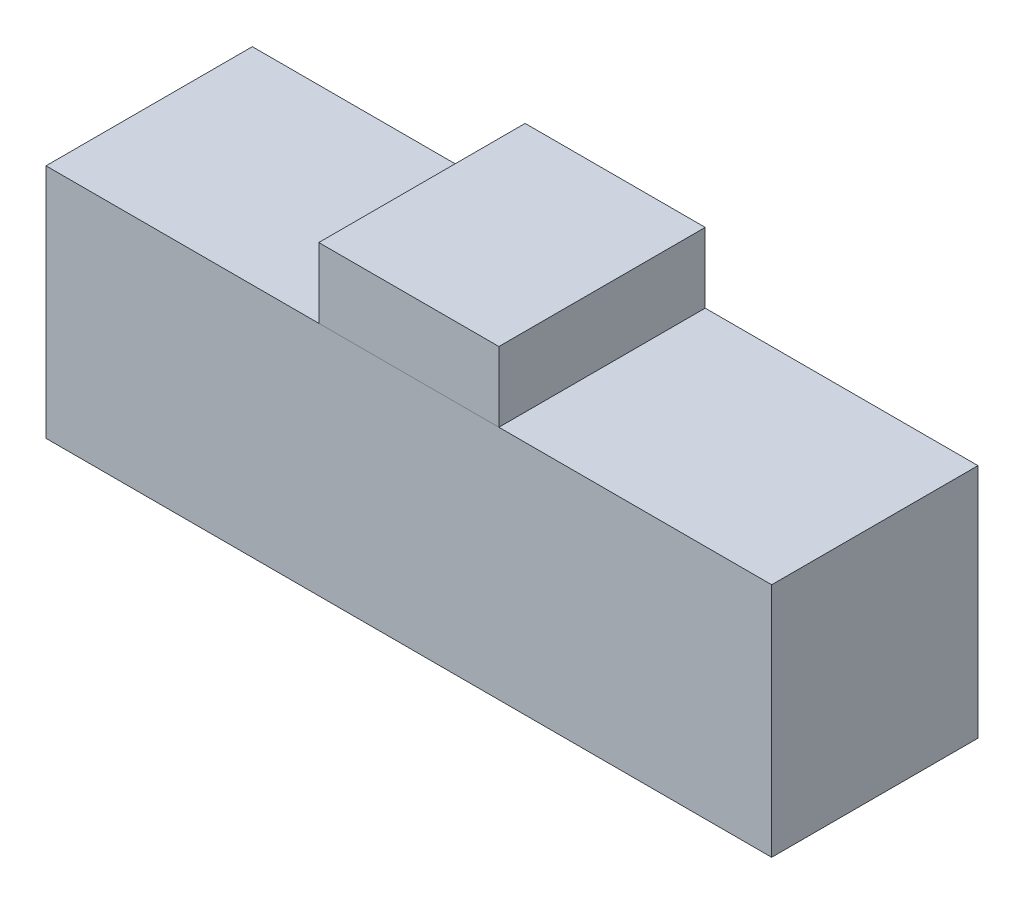
SolidWorks part; units mm, degrees
ref_plane "Front Plane" through (0, 0, 0) normal (0, 0, 1) x (1, 0, 0)
ref_plane "Top Plane" through (0, 0, 0) normal (0, 1, 0) x (1, 0, 0)
ref_plane "Right Plane" through (0, 0, 0) normal (1, 0, 0) x (0, 0, -1)
sketch "Sketch1" plane through (0, 0, 0) normal (0, 0, 1) x (1, 0, 0)
  line L1 (0, 0) -> (105.41, 0)
  line L2 (0, 0) -> (0, 34.29)
  line L3 (0, 34.29) -> (105.41, 34.29)
  line L4 (105.41, 0) -> (105.41, 34.29)
  dimension "D1" = 105.41
  dimension "D2" = 34.29
extrude "Boss-Extrude1" add sketch "Sketch1" along normal blind 29.972
sketch "Sketch2" plane through (0, 34.29, 0) normal (0, 1, 0) x (1, 0, 0)
  line L0 (105.41, 0) -> (0, 0) construction
  line L1 (65.786, -29.972) -> (39.624, -29.972)
  line L2 (65.786, -29.972) -> (65.786, 0)
  line L3 (65.786, 0) -> (39.624, 0)
  line L4 (39.624, -29.972) -> (39.624, 0)
  line L5 (105.41, -29.972) -> (0, -29.972) construction
  point P10 (52.705, 0)
  point P13 (52.705, 0)
  dimension "D1" = 26.162
extrude "Boss-Extrude2" add sketch "Sketch2" along normal blind 10.16 separate body
